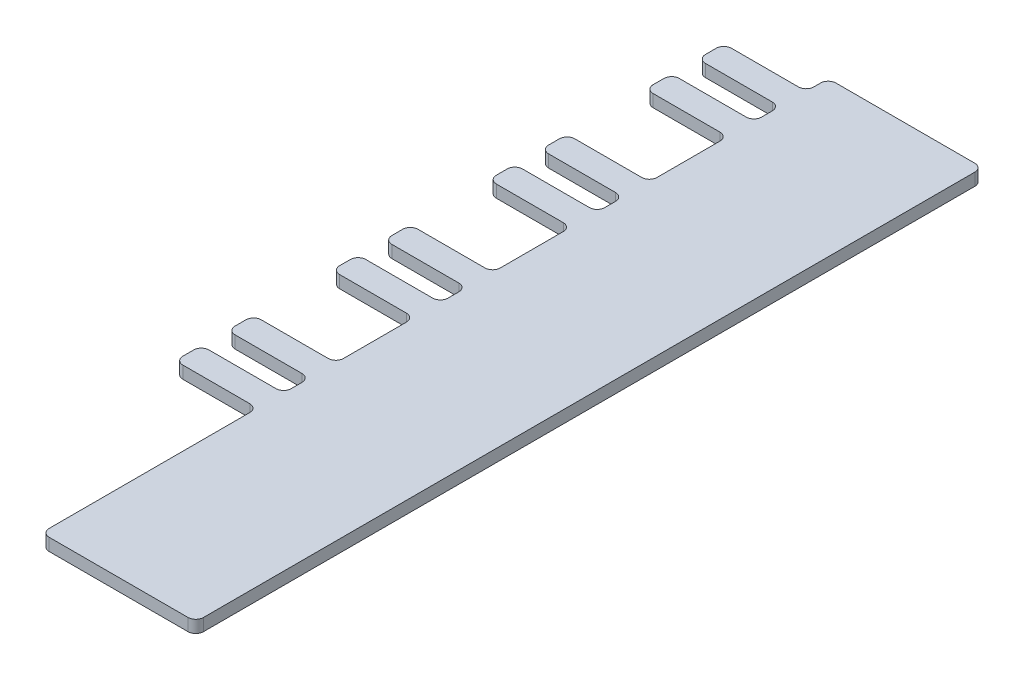
SolidWorks part; units mm, degrees
ref_plane "Front Plane" through (0, 0, 0) normal (0, 0, 1) x (1, 0, 0)
ref_plane "Top Plane" through (0, 0, 0) normal (0, 1, 0) x (1, 0, 0)
ref_plane "Right Plane" through (0, 0, 0) normal (1, 0, 0) x (0, 0, -1)
sketch "Sketch1" plane through (0, 0, 0) normal (0, 1, 0) x (1, 0, 0)
  line L0 (-0.75, 21) -> (-7.25, 21)
  line L2 (0, 20.25) -> (0, 0.75)
  line L5 (-8, 22.27) -> (5.7163, 22.27) construction
  line L7 (-8, 21.75) -> (-8, 22.79)
  line L8 (-7.25, 23.54) -> (-0.7462, 23.54)
  line L12 (0, 25.33) -> (0, 24.2149)
  line L17 (-0.75, 26.08) -> (-7.25, 26.08)
  line L22 (-8, 26.83) -> (-8, 27.87)
  line L27 (-7.25, 28.62) -> (-0.7462, 28.62)
  line L56 (14.25, 0) -> (0.75, 0)
  line L84 (0, 30.41) -> (0, 10.91) [skipped]
  line L85 (-0.75, 31.16) -> (-7.25, 31.16) [skipped]
  line L86 (-8, 31.91) -> (-8, 32.95) [skipped]
  line L87 (-7.25, 33.7) -> (-0.7462, 33.7) [skipped]
  line L88 (0, 35.49) -> (0, 15.99) [skipped]
  line L89 (-0.75, 36.24) -> (-7.25, 36.24) [skipped]
  line L90 (-8, 36.99) -> (-8, 38.03) [skipped]
  line L91 (-7.25, 38.78) -> (-0.7462, 38.78) [skipped]
  line L92 (0, 40.57) -> (0, 21.07) [skipped]
  line L93 (-0.75, 41.32) -> (-7.25, 41.32) [skipped]
  line L94 (-8, 42.07) -> (-8, 43.11) [skipped]
  line L95 (-7.25, 43.86) -> (-0.7462, 43.86) [skipped]
  line L96 (0, 45.65) -> (0, 26.15) [skipped]
  line L97 (-0.75, 46.4) -> (-7.25, 46.4) [skipped]
  line L98 (-8, 47.15) -> (-8, 48.19) [skipped]
  line L99 (-7.25, 48.94) -> (-0.7462, 48.94) [skipped]
  line L100 (0, 50.73) -> (0, 31.23) [skipped]
  line L101 (-0.75, 51.48) -> (-7.25, 51.48) [skipped]
  line L102 (-8, 52.23) -> (-8, 53.27) [skipped]
  line L103 (-7.25, 54.02) -> (-0.7462, 54.02) [skipped]
  line L104 (0, 55.81) -> (0, 36.31) [skipped]
  line L105 (-0.75, 56.56) -> (-7.25, 56.56) [skipped]
  line L106 (-8, 57.31) -> (-8, 58.35) [skipped]
  line L107 (-7.25, 59.1) -> (-0.7462, 59.1) [skipped]
  line L108 (0, 60.89) -> (0, 41.39) [skipped]
  line L109 (-0.75, 61.64) -> (-7.25, 61.64) [skipped]
  line L110 (-8, 62.39) -> (-8, 63.43) [skipped]
  line L111 (-7.25, 64.18) -> (-0.7462, 64.18) [skipped]
  line L112 (0, 65.97) -> (0, 46.47) [skipped]
  line L113 (-0.75, 66.72) -> (-7.25, 66.72) [skipped]
  line L114 (-8, 67.47) -> (-8, 68.51) [skipped]
  line L115 (-7.25, 69.26) -> (-0.7462, 69.26) [skipped]
  line L116 (-0.75, 36.24) -> (-7.25, 36.24)
  line L117 (-8, 36.99) -> (-8, 38.03)
  line L118 (-7.25, 38.78) -> (-0.7462, 38.78)
  line L119 (0, 40.57) -> (0, 39.4549)
  line L120 (-0.75, 41.32) -> (-7.25, 41.32)
  line L121 (-8, 42.07) -> (-8, 43.11)
  line L122 (-7.25, 43.86) -> (-0.7462, 43.86)
  line L123 (-0.75, 51.48) -> (-7.25, 51.48)
  line L124 (-8, 52.23) -> (-8, 53.27)
  line L125 (-7.25, 54.02) -> (-0.7462, 54.02)
  line L126 (0, 55.81) -> (0, 54.6949)
  line L127 (-0.75, 56.56) -> (-7.25, 56.56)
  line L128 (-8, 57.31) -> (-8, 58.35)
  line L129 (-7.25, 59.1) -> (-0.7462, 59.1)
  line L130 (-0.75, 66.72) -> (-7.25, 66.72)
  line L131 (-8, 67.47) -> (-8, 68.51)
  line L132 (-7.25, 69.26) -> (-0.7462, 69.26)
  line L133 (0, 71.05) -> (0, 69.9349)
  line L134 (-0.75, 71.8) -> (-7.25, 71.8)
  line L135 (-8, 72.55) -> (-8, 73.59)
  line L136 (-7.25, 74.34) -> (-0.7462, 74.34)
  line L137 (0, 35.49) -> (0, 29.2949)
  line L138 (0, 44.5349) -> (0, 50.73)
  line L139 (0, 59.7749) -> (0, 65.97)
  line L140 (0, 75.0149) -> (0, 75.74)
  line L141 (0.75, 76.49) -> (14.25, 76.49)
  line L142 (15, 75.74) -> (15, 0.75)
  arc A0 (-0.7462, 23.54) -> (0, 24.2149) centre (-0.7462, 24.29) ccw
  arc A1 (-8, 22.79) -> (-7.25, 23.54) centre (-7.25, 22.79) cw
  arc A2 (-7.25, 21) -> (-8, 21.75) centre (-7.25, 21.75) cw
  arc A3 (0, 0.75) -> (0.75, 0) centre (0.75, 0.75) ccw
  arc A4 (-0.75, 21) -> (0, 20.25) centre (-0.75, 20.25) cw
  arc A5 (15, 0.75) -> (14.25, 0) centre (14.25, 0.75) cw
  arc A6 (-0.75, 26.08) -> (0, 25.33) centre (-0.75, 25.33) cw
  arc A7 (-7.25, 26.08) -> (-8, 26.83) centre (-7.25, 26.83) cw
  arc A8 (-8, 27.87) -> (-7.25, 28.62) centre (-7.25, 27.87) cw
  arc A9 (-0.7462, 28.62) -> (0, 29.2949) centre (-0.7462, 29.37) ccw
  arc A44 (-0.75, 31.16) -> (0, 30.41) centre (-0.75, 30.41) cw [skipped]
  arc A45 (-7.25, 31.16) -> (-8, 31.91) centre (-7.25, 31.91) cw [skipped]
  arc A46 (-8, 32.95) -> (-7.25, 33.7) centre (-7.25, 32.95) cw [skipped]
  arc A47 (-0.7462, 33.7) -> (0, 34.3749) centre (-0.7462, 34.45) ccw [skipped]
  arc A48 (-0.75, 36.24) -> (0, 35.49) centre (-0.75, 35.49) cw [skipped]
  arc A49 (-7.25, 36.24) -> (-8, 36.99) centre (-7.25, 36.99) cw [skipped]
  arc A50 (-8, 38.03) -> (-7.25, 38.78) centre (-7.25, 38.03) cw [skipped]
  arc A51 (-0.7462, 38.78) -> (0, 39.4549) centre (-0.7462, 39.53) ccw [skipped]
  arc A52 (-0.75, 41.32) -> (0, 40.57) centre (-0.75, 40.57) cw [skipped]
  arc A53 (-7.25, 41.32) -> (-8, 42.07) centre (-7.25, 42.07) cw [skipped]
  arc A54 (-8, 43.11) -> (-7.25, 43.86) centre (-7.25, 43.11) cw [skipped]
  arc A55 (-0.7462, 43.86) -> (0, 44.5349) centre (-0.7462, 44.61) ccw [skipped]
  arc A56 (-0.75, 46.4) -> (0, 45.65) centre (-0.75, 45.65) cw [skipped]
  arc A57 (-7.25, 46.4) -> (-8, 47.15) centre (-7.25, 47.15) cw [skipped]
  arc A58 (-8, 48.19) -> (-7.25, 48.94) centre (-7.25, 48.19) cw [skipped]
  arc A59 (-0.7462, 48.94) -> (0, 49.6149) centre (-0.7462, 49.69) ccw [skipped]
  arc A60 (-0.75, 51.48) -> (0, 50.73) centre (-0.75, 50.73) cw [skipped]
  arc A61 (-7.25, 51.48) -> (-8, 52.23) centre (-7.25, 52.23) cw [skipped]
  arc A62 (-8, 53.27) -> (-7.25, 54.02) centre (-7.25, 53.27) cw [skipped]
  arc A63 (-0.7462, 54.02) -> (0, 54.6949) centre (-0.7462, 54.77) ccw [skipped]
  arc A64 (-0.75, 56.56) -> (0, 55.81) centre (-0.75, 55.81) cw [skipped]
  arc A65 (-7.25, 56.56) -> (-8, 57.31) centre (-7.25, 57.31) cw [skipped]
  arc A66 (-8, 58.35) -> (-7.25, 59.1) centre (-7.25, 58.35) cw [skipped]
  arc A67 (-0.7462, 59.1) -> (0, 59.7749) centre (-0.7462, 59.85) ccw [skipped]
  arc A68 (-0.75, 61.64) -> (0, 60.89) centre (-0.75, 60.89) cw [skipped]
  arc A69 (-7.25, 61.64) -> (-8, 62.39) centre (-7.25, 62.39) cw [skipped]
  arc A70 (-8, 63.43) -> (-7.25, 64.18) centre (-7.25, 63.43) cw [skipped]
  arc A71 (-0.7462, 64.18) -> (0, 64.8549) centre (-0.7462, 64.93) ccw [skipped]
  arc A72 (-0.75, 66.72) -> (0, 65.97) centre (-0.75, 65.97) cw [skipped]
  arc A73 (-7.25, 66.72) -> (-8, 67.47) centre (-7.25, 67.47) cw [skipped]
  arc A74 (-8, 68.51) -> (-7.25, 69.26) centre (-7.25, 68.51) cw [skipped]
  arc A75 (-0.7462, 69.26) -> (0, 69.9349) centre (-0.7462, 70.01) ccw [skipped]
  arc A76 (-0.7462, 38.78) -> (0, 39.4549) centre (-0.7462, 39.53) ccw
  arc A77 (-8, 38.03) -> (-7.25, 38.78) centre (-7.25, 38.03) cw
  arc A78 (-7.25, 36.24) -> (-8, 36.99) centre (-7.25, 36.99) cw
  arc A79 (-0.75, 36.24) -> (0, 35.49) centre (-0.75, 35.49) cw
  arc A80 (-0.75, 41.32) -> (0, 40.57) centre (-0.75, 40.57) cw
  arc A81 (-7.25, 41.32) -> (-8, 42.07) centre (-7.25, 42.07) cw
  arc A82 (-8, 43.11) -> (-7.25, 43.86) centre (-7.25, 43.11) cw
  arc A83 (-0.7462, 43.86) -> (0, 44.5349) centre (-0.7462, 44.61) ccw
  arc A84 (-0.7462, 54.02) -> (0, 54.6949) centre (-0.7462, 54.77) ccw
  arc A85 (-8, 53.27) -> (-7.25, 54.02) centre (-7.25, 53.27) cw
  arc A86 (-7.25, 51.48) -> (-8, 52.23) centre (-7.25, 52.23) cw
  arc A87 (-0.75, 51.48) -> (0, 50.73) centre (-0.75, 50.73) cw
  arc A88 (-0.75, 56.56) -> (0, 55.81) centre (-0.75, 55.81) cw
  arc A89 (-7.25, 56.56) -> (-8, 57.31) centre (-7.25, 57.31) cw
  arc A90 (-8, 58.35) -> (-7.25, 59.1) centre (-7.25, 58.35) cw
  arc A91 (-0.7462, 59.1) -> (0, 59.7749) centre (-0.7462, 59.85) ccw
  arc A92 (-0.7462, 69.26) -> (0, 69.9349) centre (-0.7462, 70.01) ccw
  arc A93 (-8, 68.51) -> (-7.25, 69.26) centre (-7.25, 68.51) cw
  arc A94 (-7.25, 66.72) -> (-8, 67.47) centre (-7.25, 67.47) cw
  arc A95 (-0.75, 66.72) -> (0, 65.97) centre (-0.75, 65.97) cw
  arc A96 (-0.75, 71.8) -> (0, 71.05) centre (-0.75, 71.05) cw
  arc A97 (-7.25, 71.8) -> (-8, 72.55) centre (-7.25, 72.55) cw
  arc A98 (-8, 73.59) -> (-7.25, 74.34) centre (-7.25, 73.59) cw
  arc A99 (-0.7462, 74.34) -> (0, 75.0149) centre (-0.7462, 75.09) ccw
  arc A100 (0, 75.74) -> (0.75, 76.49) centre (0.75, 75.74) cw
  arc A101 (14.25, 76.49) -> (15, 75.74) centre (14.25, 75.74) cw
  point P0 (0, 0)
  point P27 (0, 23.54)
  point P46 (0, 38.78)
  point P48 (-8, 23.54)
  point P69 (-8, 21)
  point P73 (0, 54.02)
  point P78 (0, 0)
  point P81 (0, 21)
  point P84 (15, 0)
  point P108 (0, 69.26)
  point P123 (-3.9981, 74.34)
  dimension "D6" = 0.75
  dimension "D7" = 0.75
  dimension "D8" = 4
  dimension "D9" = 10.16
  dimension "D11" = 0.75
  dimension "D1" = 2.54
  dimension "D2" = 8
  dimension "D3" = 10
  dimension "D4" = 21
  dimension "D5" = 15
  dimension "D10" = 5.08
  dimension "D12" = 2.15
extrude "Boss-Extrude1" add sketch "Sketch1" along normal blind 1.2
